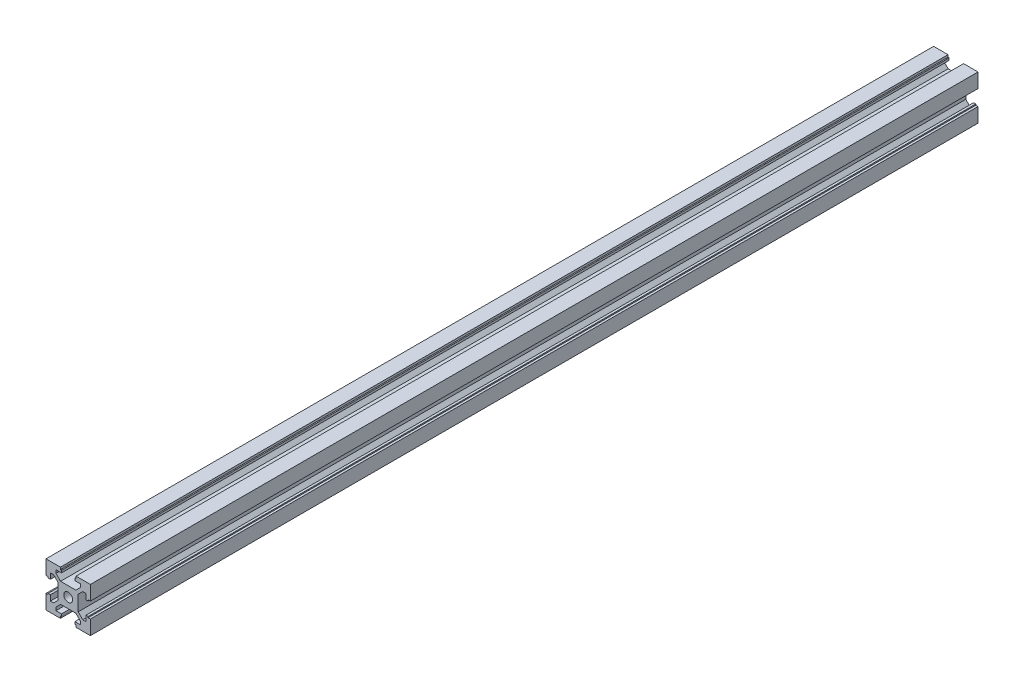
SolidWorks part; units mm, degrees
ref_plane "Front Plane" through (0, 0, 0) normal (0, 0, 1) x (1, 0, 0)
ref_plane "Top Plane" through (0, 0, 0) normal (0, 1, 0) x (1, 0, 0)
ref_plane "Right Plane" through (0, 0, 0) normal (1, 0, 0) x (0, 0, -1)
sketch "Sketch1" plane through (0, 0, 0) normal (0, 0, 1) x (1, 0, 0)
  line L0 (0, 10) -> (0, -4.5007) construction
  line L1 (-10, -10) -> (-3.5, -10)
  line L2 (-10, -10) -> (-10, -3.5)
  line L3 (-10, 10) -> (-3.5, 10)
  line L4 (10, -10) -> (10, -3.5)
  line L5 (-10, -10) -> (10, 10) construction
  line L6 (-10, 10) -> (10, -10) construction
  line L7 (-10, 0) -> (10, 0) construction
  line L8 (-3.5, 10) -> (-3.5, 9)
  line L9 (-3.44, -4.5007) -> (3.44, -4.5007)
  line L10 (-4.5007, -3.44) -> (-4.5007, 3.44)
  line L11 (-3.44, 4.5007) -> (3.44, 4.5007)
  line L12 (4.5007, -3.44) -> (4.5007, 3.44)
  line L13 (-10, -10) -> (10, 10) construction
  line L14 (-10, 10) -> (10, -10) construction
  line L15 (-3.5, 9) -> (-3, 9)
  line L16 (-3, 9) -> (-3, 8)
  line L17 (-3, 8) -> (-5.5, 8)
  line L18 (-5.5, 8) -> (-5.5, 6.5607)
  line L19 (-5.5, 6.5607) -> (-3.44, 4.5007)
  line L20 (3.5, 10) -> (10, 10)
  line L21 (3.5, 9) -> (3, 9)
  line L22 (5.5, 6.5607) -> (3.44, 4.5007)
  line L23 (5.5, 8) -> (5.5, 6.5607)
  line L24 (3, 8) -> (5.5, 8)
  line L25 (3, 9) -> (3, 8)
  line L26 (3.5, 10) -> (3.5, 9)
  line L27 (-3.5, 10) -> (3.5, 10) construction
  line L28 (5.5, -6.5607) -> (3.44, -4.5007)
  line L29 (5.5, -8) -> (5.5, -6.5607)
  line L30 (3, -8) -> (5.5, -8)
  line L31 (3, -9) -> (3, -8)
  line L32 (3.5, -9) -> (3, -9)
  line L33 (3.5, -10) -> (3.5, -9)
  line L34 (-3.5, -9) -> (-3, -9)
  line L35 (-5.5, -6.5607) -> (-3.44, -4.5007)
  line L36 (-5.5, -8) -> (-5.5, -6.5607)
  line L37 (-3, -8) -> (-5.5, -8)
  line L38 (-3, -9) -> (-3, -8)
  line L39 (-3.5, -10) -> (-3.5, -9)
  line L40 (-6.5607, -5.5) -> (-4.5007, -3.44)
  line L41 (-8, -5.5) -> (-6.5607, -5.5)
  line L42 (-8, -3) -> (-8, -5.5)
  line L43 (-10, -3.5) -> (-9, -3.5)
  line L44 (-9, -3) -> (-8, -3)
  line L45 (-9, -3.5) -> (-9, -3)
  line L46 (6.5607, -5.5) -> (4.5007, -3.44)
  line L47 (8, -5.5) -> (6.5607, -5.5)
  line L48 (8, -3) -> (8, -5.5)
  line L49 (9, -3) -> (8, -3)
  line L50 (9, -3.5) -> (9, -3)
  line L51 (10, -3.5) -> (9, -3.5)
  line L52 (-6.5607, 5.5) -> (-4.5007, 3.44)
  line L53 (-8, 5.5) -> (-6.5607, 5.5)
  line L54 (-8, 3) -> (-8, 5.5)
  line L55 (-9, 3) -> (-8, 3)
  line L56 (-9, 3.5) -> (-9, 3)
  line L57 (-10, 3.5) -> (-9, 3.5)
  line L58 (10, 3.5) -> (9, 3.5)
  line L59 (9, 3.5) -> (9, 3)
  line L60 (9, 3) -> (8, 3)
  line L61 (8, 3) -> (8, 5.5)
  line L62 (8, 5.5) -> (6.5607, 5.5)
  line L63 (6.5607, 5.5) -> (4.5007, 3.44)
  line L64 (10, 3.5) -> (10, 10)
  line L65 (-10, 3.5) -> (-10, 10)
  line L66 (-10, 3.5) -> (-10, -3.5) construction
  line L67 (10, 3.5) -> (10, -3.5) construction
  line L68 (3.5, -10) -> (10, -10)
  line L69 (-3.5, -10) -> (3.5, -10) construction
  circle A0 centre (0, 0) radius 2
  point P0 (0, 0)
  point P10 (0, 0)
  dimension "D10" = 4
  dimension "D1" = 20
  dimension "D2" = 14.5007
  dimension "D3" = 0.75
  dimension "D4" = 3.5
  dimension "D5" = 3
  dimension "D6" = 1
  dimension "D7" = 1
  dimension "D8" = 3.44
  dimension "D9" = 5.5
extrude "Boss-Extrude1" add sketch "Sketch1" along normal blind 400
